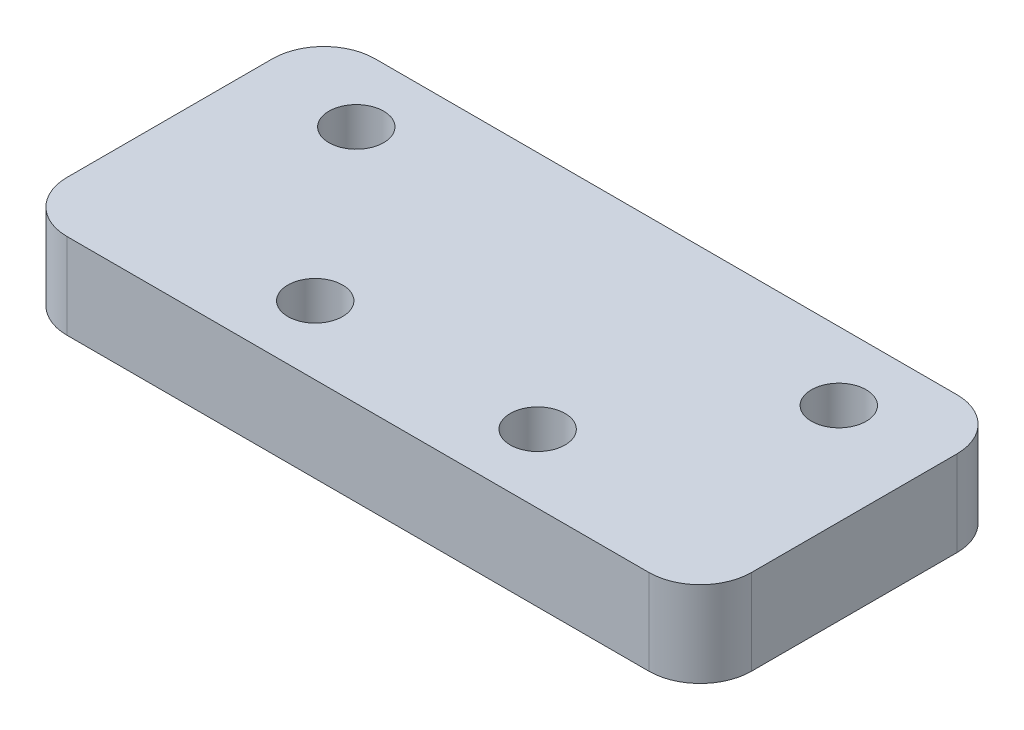
SolidWorks part; units mm, degrees
ref_plane "Front Plane" through (0, 0, 0) normal (0, 0, 1) x (1, 0, 0)
ref_plane "Top Plane" through (0, 0, 0) normal (0, 1, 0) x (1, 0, 0)
ref_plane "Right Plane" through (0, 0, 0) normal (1, 0, 0) x (0, 0, -1)
sketch "Sketch2" plane through (0, 0, 0) normal (0, 1, 0) x (1, 0, 0)
  line L0 (5.9, 14) -> (34.1, 14) construction
  line L1 (0, 0) -> (40, 0)
  line L2 (0, 0) -> (0, 18)
  line L3 (0, 18) -> (40, 18)
  line L4 (40, 0) -> (40, 18)
  line L5 (13.5, 4) -> (26.5, 4) construction
  circle A0 centre (5.9, 14) radius 1.6
  circle A1 centre (34.1, 14) radius 1.6
  circle A2 centre (13.5, 4) radius 1.6
  circle A3 centre (26.5, 4) radius 1.6
  dimension "D3" = 3.2
  dimension "D4" = 3.2
  dimension "D8" = 3.2
  dimension "D9" = 3.2
  dimension "D11" = 13.5
  dimension "D12" = 4
  dimension "D1" = 40
  dimension "D2" = 18
  dimension "D5" = 4
  dimension "D6" = 28.2
  dimension "D7" = 5.9
  dimension "D10" = 13
extrude "Boss-Extrude1" add sketch "Sketch2" along normal blind 5
fillet "Fillet1" radius 3 4 edges at (40, 2.5, -18) (40, 2.5, 0) (0, 2.5, 0) (0, 2.5, -18)
